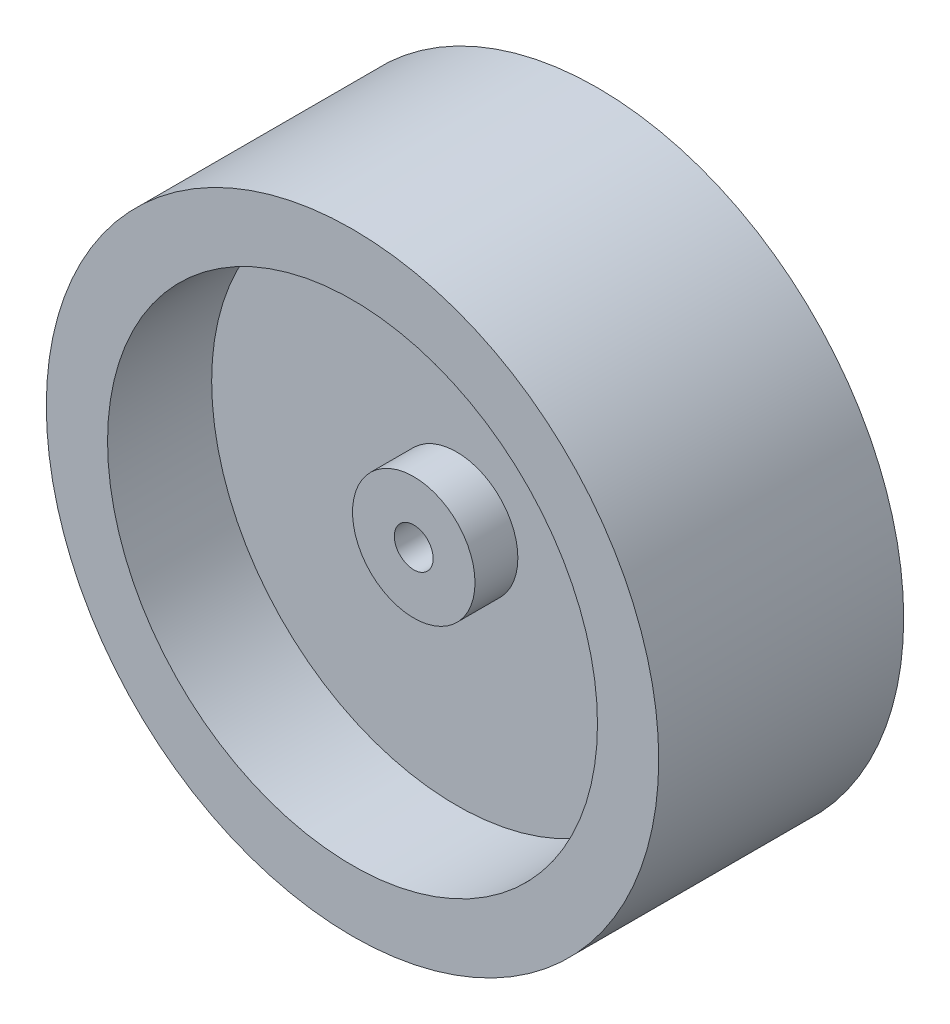
SolidWorks part; units mm, degrees
ref_plane "Front Plane" through (0, 0, 0) normal (0, 0, 1) x (1, 0, 0)
ref_plane "Top Plane" through (0, 0, 0) normal (0, 1, 0) x (1, 0, 0)
ref_plane "Right Plane" through (0, 0, 0) normal (1, 0, 0) x (0, 0, -1)
sketch "Sketch1" plane through (0, 0, 0) normal (0, 0, 1) x (1, 0, 0)
  circle A0 centre (0, 0) radius 25
  dimension "D1" = 50
extrude "Boss-Extrude1" add sketch "Sketch1" along normal mid plane 3
sketch "Sketch2" plane through (0, 0, 0) normal (0, 0, 1) x (1, 0, 0)
  circle A0 centre (0, 0) radius 25 construction
  circle A1 centre (0, 0) radius 25
  circle A2 centre (0, 0) radius 20
  dimension "D1" = 5
extrude "Boss-Extrude2" add sketch "Sketch2" along normal mid plane 20
sketch "Sketch3" plane through (0, 0, 0) normal (0, 0, 1) x (1, 0, 0)
  circle A0 centre (0, 0) radius 5
  dimension "D1" = 10
extrude "Boss-Extrude3" add sketch "Sketch3" along normal mid plane 10
sketch "Sketch4" plane through (0, 0, -5) normal (0, 0, -1) x (-1, 0, 0)
  circle A0 centre (0, 0) radius 1.585
  dimension "D1" = 3.17
extrude "Cut-Extrude1" cut sketch "Sketch4" against normal up to surface (10 mm away) up to face at (5, 0, 5)
